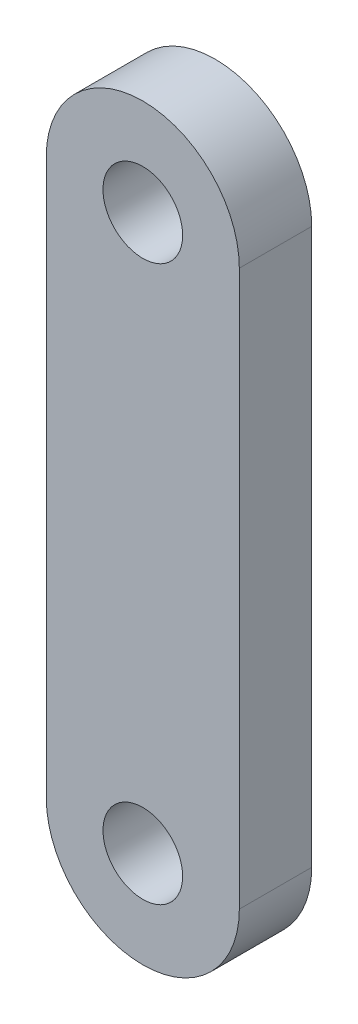
SolidWorks part; units mm, degrees
ref_plane "前视基准面" through (0, 0, 0) normal (0, 0, 1) x (1, 0, 0)
ref_plane "上视基准面" through (0, 0, 0) normal (0, 1, 0) x (1, 0, 0)
ref_plane "右视基准面" through (0, 0, 0) normal (1, 0, 0) x (0, 0, -1)
sketch "草图1" plane through (0, 0, 0) normal (0, 0, 1) x (1, 0, 0)
  line L0 (0, 11.5) -> (0, -11.5) construction
  line L2 (4, 11.5) -> (4, -11.5)
  line L3 (-4, 11.5) -> (-4, -11.5)
  arc A0 (4, 11.5) -> (-4, 11.5) centre (0, 11.5) ccw
  arc A1 (-4, -11.5) -> (4, -11.5) centre (0, -11.5) ccw
  circle A2 centre (0, 11.5) radius 1.65
  circle A3 centre (0, -11.5) radius 1.65
  point P5 (0, 0)
  dimension "D2" = 4
  dimension "D3" = 3.3
  dimension "D4" = 3.3
  dimension "D1" = 23
extrude "凸台-拉伸1" add sketch "草图1" along normal blind 3
